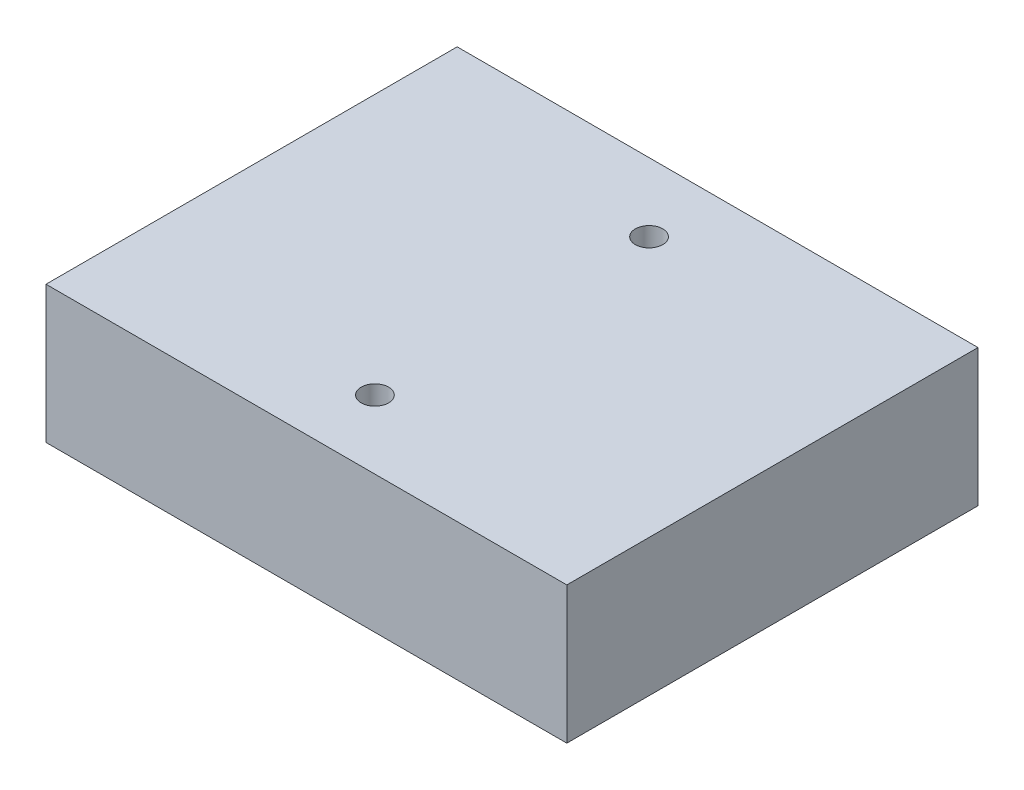
SolidWorks part; units mm, degrees
ref_plane "Front Plane" through (0, 0, 0) normal (0, 0, 1) x (1, 0, 0)
ref_plane "Top Plane" through (0, 0, 0) normal (0, 1, 0) x (1, 0, 0)
ref_plane "Right Plane" through (0, 0, 0) normal (1, 0, 0) x (0, 0, -1)
sketch "Sketch1" plane through (0, 0, 0) normal (0, 1, 0) x (1, 0, 0)
  line L1 (27.5142, 58.7513) -> (103.5142, 58.7513)
  line L2 (27.5142, 58.7513) -> (27.5142, -1.2487)
  line L3 (27.5142, -1.2487) -> (103.5142, -1.2487)
  line L4 (103.5142, 58.7513) -> (103.5142, -1.2487)
  circle A0 centre (65.5142, 8.7513) radius 2
  circle A1 centre (65.5142, 48.7513) radius 2
  dimension "D6" = 4
  dimension "D7" = 4
  dimension "D1" = 76
  dimension "D2" = 60
  dimension "D3" = 38
  dimension "D4" = 10
  dimension "D5" = 10
extrude "Boss-Extrude1" add sketch "Sketch1" along normal blind 20
